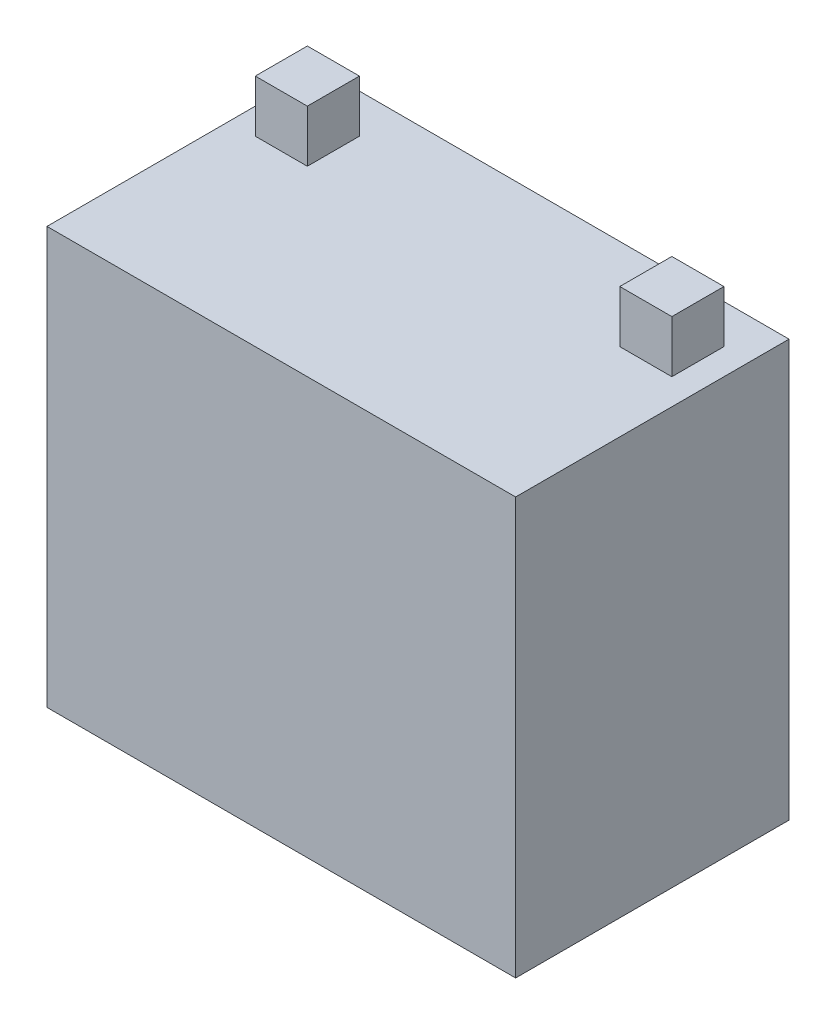
SolidWorks part; units mm, degrees
ref_plane "Front Plane" through (0, 0, 0) normal (0, 0, 1) x (1, 0, 0)
ref_plane "Top Plane" through (0, 0, 0) normal (0, 1, 0) x (1, 0, 0)
ref_plane "Right Plane" through (0, 0, 0) normal (1, 0, 0) x (0, 0, -1)
sketch "Sketch1" plane through (0, 0, 0) normal (0, 1, 0) x (1, 0, 0)
  line L1 (-114.3, -66.675) -> (114.3, -66.675)
  line L2 (-114.3, -66.675) -> (-114.3, 66.675)
  line L3 (-114.3, 66.675) -> (114.3, 66.675)
  line L4 (114.3, -66.675) -> (114.3, 66.675)
  line L5 (-114.3, -66.675) -> (114.3, 66.675) construction
  line L6 (-114.3, 66.675) -> (114.3, -66.675) construction
  point P0 (0, 0)
  dimension "D1" = 133.35
  dimension "D2" = 228.6
extrude "Boss-Extrude1" add sketch "Sketch1" along normal mid plane 203.2
sketch "Sketch2" plane through (0, 101.6, 0) normal (0, 1, 0) x (1, 0, 0)
  line L0 (0, 0) -> (0, 50000) construction
  line L1 (-101.6, 47.625) -> (-76.2, 47.625)
  line L2 (-101.6, 47.625) -> (-101.6, 22.225)
  line L3 (-101.6, 22.225) -> (-76.2, 22.225)
  line L4 (-76.2, 47.625) -> (-76.2, 22.225)
  line L5 (-101.6, 47.625) -> (-76.2, 22.225) construction
  line L6 (-101.6, 22.225) -> (-76.2, 47.625) construction
  line L7 (76.2, 22.225) -> (101.6, 22.225)
  line L8 (76.2, 22.225) -> (76.2, 47.625)
  line L9 (76.2, 47.625) -> (101.6, 47.625)
  line L10 (101.6, 22.225) -> (101.6, 47.625)
  line L11 (76.2, 22.225) -> (101.6, 47.625) construction
  line L12 (76.2, 47.625) -> (101.6, 22.225) construction
  line L13 (-114.3, -66.675) -> (114.3, -66.675) construction
  point P0 (-88.9, 34.925)
  point P5 (88.9, 34.925)
  dimension "D1" = 25.4
  dimension "D2" = 101.6
  dimension "D3" = 152.4
  dimension "D4" = 88.9
extrude "Boss-Extrude2" add sketch "Sketch2" along normal blind 25.4
